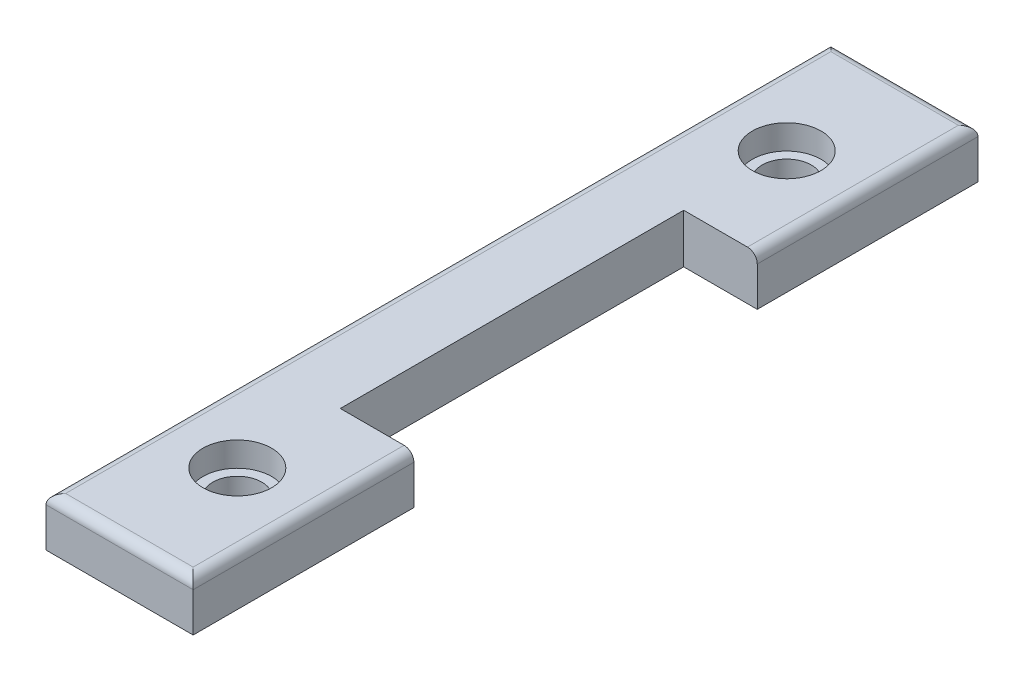
SolidWorks part; units mm, degrees
ref_plane "Front Plane" through (0, 0, 0) normal (0, 0, 1) x (1, 0, 0)
ref_plane "Top Plane" through (0, 0, 0) normal (0, 1, 0) x (1, 0, 0)
ref_plane "Right Plane" through (0, 0, 0) normal (1, 0, 0) x (0, 0, -1)
sketch "Sketch1" plane through (0, 0, 0) normal (0, 1, 0) x (1, 0, 0)
  line L1 (-7.5, -40) -> (7.5, -40)
  line L2 (-7.5, -40) -> (-7.5, 40)
  line L3 (-7.5, 40) -> (7.5, 40)
  line L4 (7.5, -40) -> (7.5, 40)
  line L5 (-7.5, -40) -> (7.5, 40) construction
  line L6 (-7.5, 40) -> (7.5, -40) construction
  point P0 (0, 0)
  dimension "D1" = 15
  dimension "D2" = 80
extrude "Boss-Extrude1" add sketch "Sketch1" along normal blind 5
sketch "Sketch2" plane through (0, 5, 0) normal (0, 1, 0) x (1, 0, 0)
  line L0 (0, -28) -> (0, 28) construction
  circle A2 centre (0, -28) radius 3.5
  point P8 (0, 0)
  dimension "D2" = 7
  dimension "D1" = 56
extrude "Cut-Extrude1" cut sketch "Sketch2" against normal blind 2.5
mirror "Mirror1" about plane through (0, 0, 0) normal (0, 0, 1) of "Cut-Extrude1"
fillet "Fillet1" radius 1 4 edges at (0, 5, 40) (7.5, 5, 0) (-7.5, 5, 0) (0, 5, -40)
sketch "Sketch3" plane through (0, 5, 0) normal (0, 1, 0) x (1, 0, 0)
  line L0 (0, -17.5) -> (0, 17.5) construction
  line L1 (7.5, 40) -> (7.5, -40) construction
  line L2 (0, 17.5) -> (7.5, 17.5)
  line L3 (0, 17.5) -> (0, -17.5)
  line L4 (0, -17.5) -> (7.5, -17.5)
  line L5 (7.5, 17.5) -> (7.5, -17.5)
  point P4 (0, 0)
  dimension "D1" = 35
extrude "Cut-Extrude2" cut sketch "Sketch3" against normal through all
sketch "Sketch4" plane through (0, 2.5, 0) normal (0, 1, 0) x (1, 0, 0)
  circle A0 centre (0, 28) radius 2.5
  circle A1 centre (0, -28) radius 2.5
  dimension "D1" = 5
  dimension "D2" = 5
extrude "Cut-Extrude3" cut sketch "Sketch4" against normal through all
